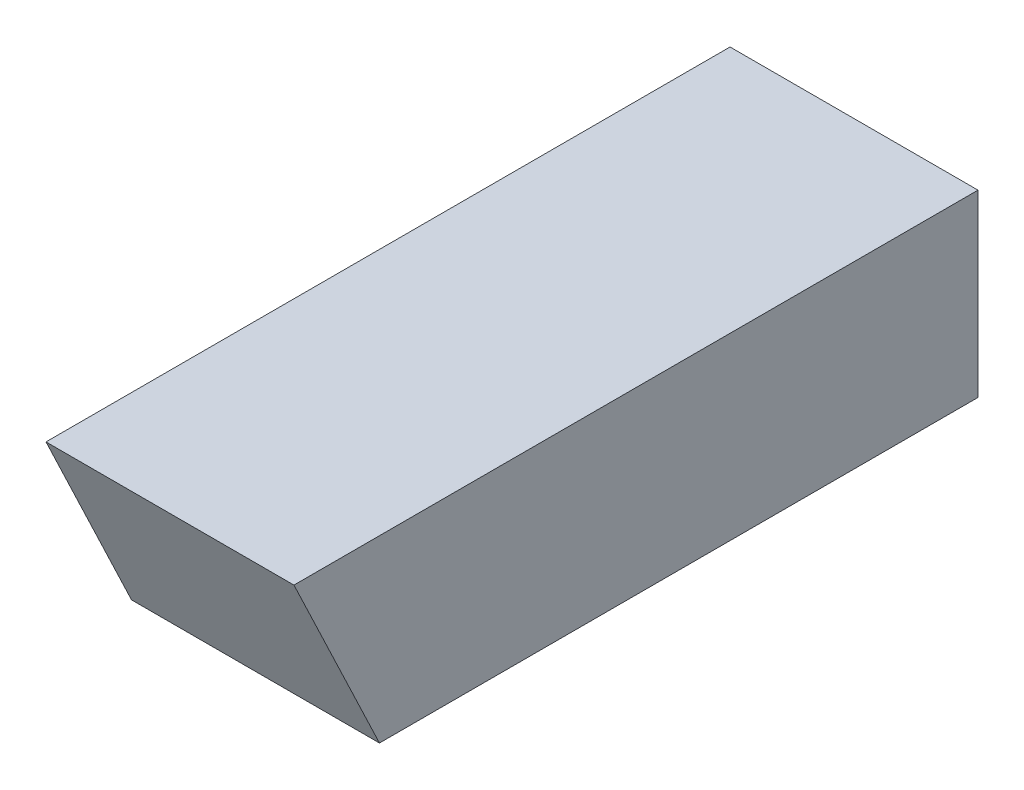
SolidWorks part; units mm, degrees
ref_plane "Front Plane" through (0, 0, 0) normal (0, 0, 1) x (1, 0, 0)
ref_plane "Top Plane" through (0, 0, 0) normal (0, 1, 0) x (1, 0, 0)
ref_plane "Right Plane" through (0, 0, 0) normal (1, 0, 0) x (0, 0, -1)
sketch "Sketch1" plane through (0, 0, 0) normal (1, 0, 0) x (0, 0, -1)
  line L0 (-350, 0) -> (0, 0)
  line L1 (0, 0) -> (0, 105)
  line L2 (0, 105) -> (-400, 105)
  line L3 (-400, 105) -> (-350, 0)
  dimension "D1" = 400
  dimension "D2" = 105
  dimension "D3" = 350
extrude "Boss-Extrude1" add sketch "Sketch1" along normal blind 145
hole_wizard "Tap Drill for 1/4-20 Tap1" positions "Sketch2" profile "Sketch3" hole size "1/4-20" standard "ANSI Inch"
sketch "Sketch2" plane through (0, 0, 0) normal (0, -1, 0) x (-1, 0, 0)
  line L0 (-72.5, -350) -> (-72.5, 0) construction
  line L1 (-145, -350) -> (0, -350) construction
  line L2 (-145, 0) -> (0, 0) construction
  point P0 (-72.5, -253)
  point P17 (-72.5, -203)
  point P18 (-72.5, -153)
  dimension "D1" = 97
  dimension "D3" = 50
  dimension "D2" = 3
sketch "Sketch3" plane through (72.5, 0, 253) normal (1, 0, 0) x (0, 0, -1)
  line L0 (0, 0) -> (0, 9.5338)
  line L1 (0, 9.5338) -> (2.5527, 8)
  line L2 (2.5527, 8) -> (2.5527, 0)
  line L5 (2.5527, 0) -> (0, 0)
  line L10 (0, 9.5338) -> (-2.5527, 8) construction
  line L11 (0, -6.35) -> (0, 107.95) construction
  dimension "Hole Dia." = 5.1054
  dimension "Hole Depth" = 8
  dimension "Drill Angle" = 118
sketch "Sketch4" plane through (0, 0, 0) normal (0, -1, 0) x (1, 0, 0)
  line L0 (72.5, 350) -> (72.5, 0) construction
  line L1 (45, 83) -> (100, 83)
  line L2 (45, 83) -> (45, 113)
  line L3 (45, 113) -> (100, 113)
  line L4 (100, 83) -> (100, 113)
  line L5 (45, 83) -> (100, 113) construction
  line L6 (45, 113) -> (100, 83) construction
  line L7 (145, 350) -> (0, 350) construction
  point P0 (72.5, 98)
  dimension "D1" = 30
  dimension "D2" = 55
  dimension "D3" = 237
extrude "Boss-Extrude2" add sketch "Sketch4" along normal blind 30
sketch "Sketch5" plane through (0, 0, 0) normal (0, -1, 0) x (1, 0, 0)
  line L0 (72.5, 288.5415) -> (608.0304, 1145.5693) construction
  line L1 (608.0304, 1145.5693) -> (-463.0304, 1145.5693) construction
  line L2 (-463.0304, 1145.5693) -> (72.5, 288.5415) construction
  line L3 (72.5, 350) -> (72.5, 1145.5693) construction
  line L4 (145, 350) -> (0, 350) construction
  dimension "D1" = 64
